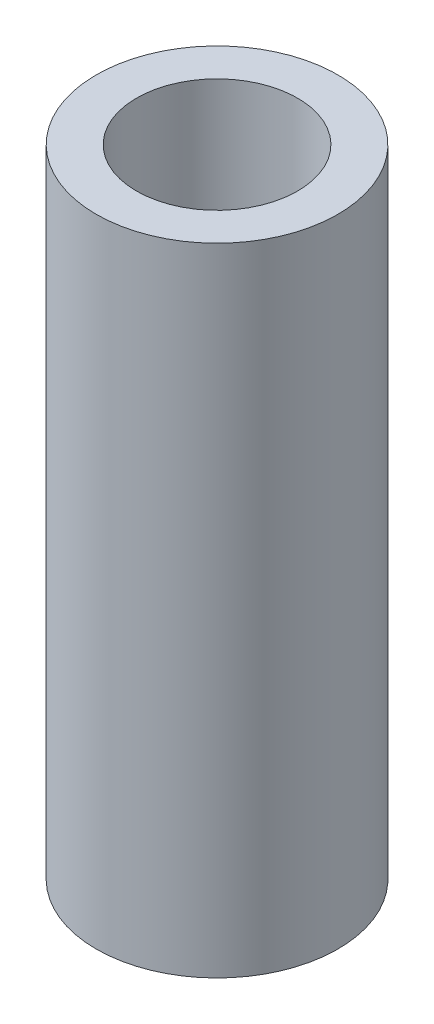
SolidWorks part; units mm, degrees
ref_plane "前视基准面" through (0, 0, 0) normal (0, 0, 1) x (1, 0, 0)
ref_plane "上视基准面" through (0, 0, 0) normal (0, 1, 0) x (1, 0, 0)
ref_plane "右视基准面" through (0, 0, 0) normal (1, 0, 0) x (0, 0, -1)
other "Configuration Table"
sketch "草图1" plane through (0, 0, 0) normal (0, 1, 0) x (1, 0, 0)
  circle A0 centre (0, 0) radius 5
  circle A1 centre (0, 0) radius 7.5
  dimension "D1" = 10
  dimension "D2" = 15
extrude "凸台-拉伸1" add sketch "草图1" along normal blind 39.5
